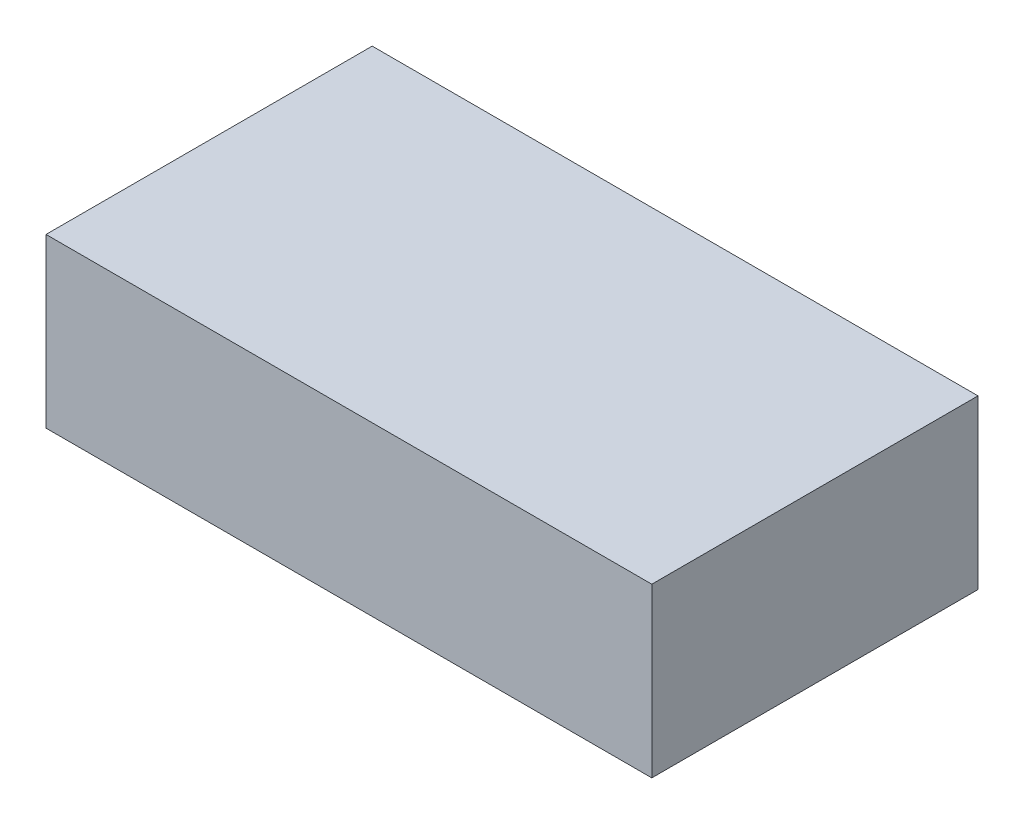
SolidWorks part; units mm, degrees
ref_plane "Front Plane" through (0, 0, 0) normal (0, 0, 1) x (1, 0, 0)
ref_plane "Top Plane" through (0, 0, 0) normal (0, 1, 0) x (1, 0, 0)
ref_plane "Right Plane" through (0, 0, 0) normal (1, 0, 0) x (0, 0, -1)
sketch "Sketch1" plane through (0, 0, 0) normal (0, 1, 0) x (1, 0, 0)
  line L1 (-32.5, 17.5) -> (32.5, 17.5)
  line L2 (-32.5, 17.5) -> (-32.5, -17.5)
  line L3 (-32.5, -17.5) -> (32.5, -17.5)
  line L4 (32.5, 17.5) -> (32.5, -17.5)
  line L5 (-32.5, 17.5) -> (32.5, -17.5) construction
  line L6 (-32.5, -17.5) -> (32.5, 17.5) construction
  point P0 (0, 0)
  dimension "D1" = 65
  dimension "D2" = 35
extrude "Boss-Extrude1" add sketch "Sketch1" along normal blind 18
